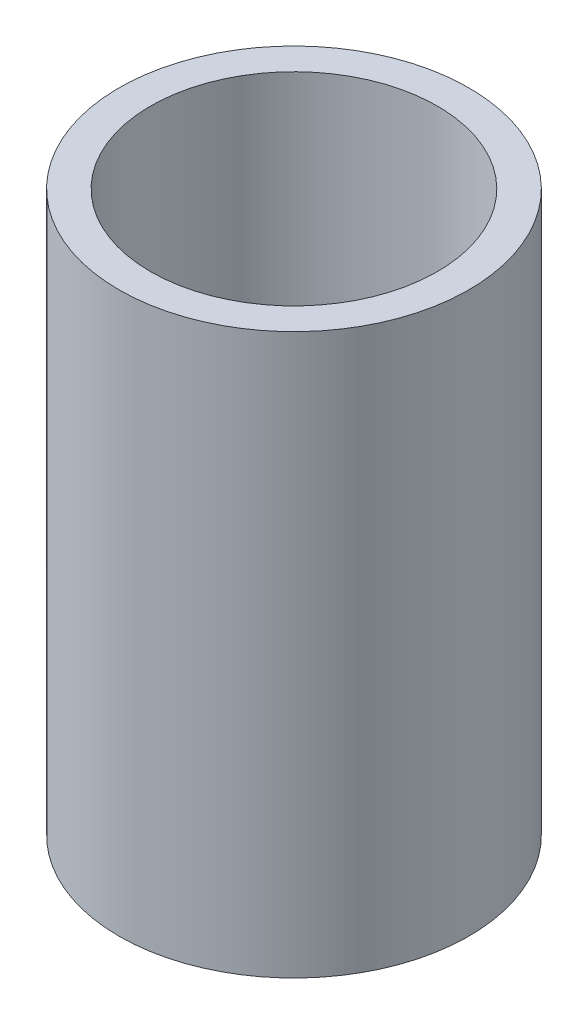
SolidWorks part; units mm, degrees
ref_plane "Front Plane" through (0, 0, 0) normal (0, 0, 1) x (1, 0, 0)
ref_plane "Top Plane" through (0, 0, 0) normal (0, 1, 0) x (1, 0, 0)
ref_plane "Right Plane" through (0, 0, 0) normal (1, 0, 0) x (0, 0, -1)
sketch "Sketch1" plane through (0, 0, 0) normal (0, 1, 0) x (1, 0, 0)
  circle A0 centre (0, 0) radius 4.1
  circle A1 centre (0, 0) radius 5
  dimension "D1" = 8.2
  dimension "D2" = 10
extrude "Boss-Extrude1" add sketch "Sketch1" along normal blind 16
